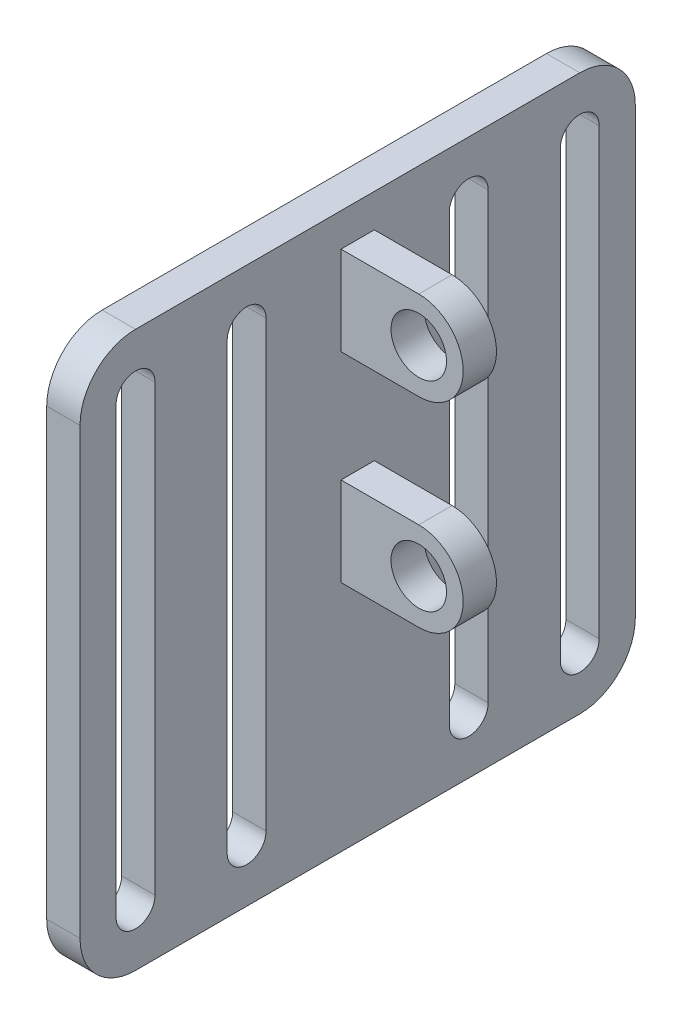
SolidWorks part; units mm, degrees
ref_plane "前视基准面" through (0, 0, 0) normal (0, 0, 1) x (1, 0, 0)
ref_plane "上视基准面" through (0, 0, 0) normal (0, 1, 0) x (1, 0, 0)
ref_plane "右视基准面" through (0, 0, 0) normal (1, 0, 0) x (0, 0, -1)
sketch "草图1" plane through (0, 0, 0) normal (1, 0, 0) x (0, 0, -1)
  line L0 (-20, 25) -> (-20, -25) construction
  line L1 (-25, 25) -> (25, 25)
  line L2 (-25, 25) -> (-25, -25)
  line L3 (-25, -25) -> (25, -25)
  line L4 (25, 25) -> (25, -25)
  line L5 (-25, 25) -> (25, -25) construction
  line L6 (-25, -25) -> (25, 25) construction
  line L7 (-10, -25) -> (-10, 25) construction
  line L8 (10, 25) -> (10, -25) construction
  line L9 (20, -25) -> (20, 25) construction
  line L10 (0, 25) -> (0, -25) construction
  line L11 (-21.75, 20) -> (-21.75, -20)
  line L12 (-18.25, -20) -> (-18.25, 20)
  line L13 (-11.75, 20) -> (-11.75, -20)
  line L14 (-8.25, 20) -> (-8.25, -20)
  line L15 (-1.75, 20) -> (-1.75, -20)
  line L16 (1.75, -20) -> (1.75, 20)
  line L17 (8.25, 20) -> (8.25, -20)
  line L18 (11.75, -20) -> (11.75, 20)
  line L19 (18.25, 20) -> (18.25, -20)
  line L20 (21.75, -20) -> (21.75, 20)
  line L21 (-25, 20) -> (25, 20) construction
  line L22 (-25, -20) -> (25, -20) construction
  circle A0 centre (-10, 20) radius 1.75
  circle A1 centre (-20, 20) radius 1.75
  circle A2 centre (-20, -20) radius 1.75
  circle A3 centre (-10, -20) radius 1.75
  circle A4 centre (0, -20) radius 1.75
  circle A5 centre (10, -20) radius 1.75
  circle A6 centre (20, -20) radius 1.75
  circle A7 centre (20, 20) radius 1.75
  circle A8 centre (10, 20) radius 1.75
  circle A9 centre (0, 20) radius 1.75
  point P0 (0, 0)
  point P58 (-20, 20)
  point P59 (0, 20)
  point P60 (10, 20)
  point P61 (20, 20)
  point P62 (20, -20)
  point P63 (20, -20)
  point P64 (20, -20)
  point P65 (21.75, -20)
  point P66 (10, -20)
  point P67 (0, -20)
  point P68 (-10, -20)
  point P69 (-20, -20)
  dimension "D7" = 3.5
  dimension "D8" = 3.5
  dimension "D9" = 3.5
  dimension "D10" = 3.5
  dimension "D11" = 3.5
  dimension "D12" = 3.5
  dimension "D13" = 3.5
  dimension "D14" = 3.5
  dimension "D15" = 3.5
  dimension "D16" = 3.5
  dimension "D17" = 5
  dimension "D18" = 5
  dimension "D1" = 50
  dimension "D2" = 50
  dimension "D3" = 5
  dimension "D4" = 5
  dimension "D5" = 10
  dimension "D6" = 10
extrude "凸台-拉伸1" add sketch "草图1" along normal blind 3 contours L4 L1 L2 L3 A9 L16 A4 L15 A8 L18 A5 L17 A7 L20 A6 L19 A3 L13 A0 L14 A2 L11 A1 L12 | A9 L15 A4 L16 | A9 | A4
sketch "草图2" plane through (0, 0, 0) normal (0, 0, 1) x (1, 0, 0)
  line L0 (0, 0) -> (25.4206, 0) construction
  line L1 (0, 18) -> (26.0129, 18) construction
  line L2 (0, 25) -> (0, -25) construction
  line L3 (10, 14) -> (0, 14)
  line L4 (10, 22) -> (0, 22)
  line L5 (0, 22) -> (0, 14)
  line L6 (10, -4) -> (0, -4)
  line L7 (0, -4) -> (0, 4)
  line L8 (0, 4) -> (10, 4)
  circle A0 centre (10, 0) radius 4
  circle A1 centre (10, 18) radius 2.5
  circle A2 centre (10, 18) radius 4
  circle A3 centre (10, 0) radius 2.5
  dimension "D1" = 5
  dimension "D2" = 8
  dimension "D3" = 8
  dimension "D4" = 5
  dimension "D5" = 10
  dimension "D6" = 10
  dimension "D7" = 18
extrude "凸台-拉伸2" add sketch "草图2" along normal mid plane 3 contours A2 L4 L5 L3 | A2 A1 | A0 A3 | A0 L8 L7 L6
fillet "圆角1" radius 5 4 edges at (1.5, -25, -25) (1.5, -25, 25) (1.5, 25, 25) (1.5, 25, -25)
